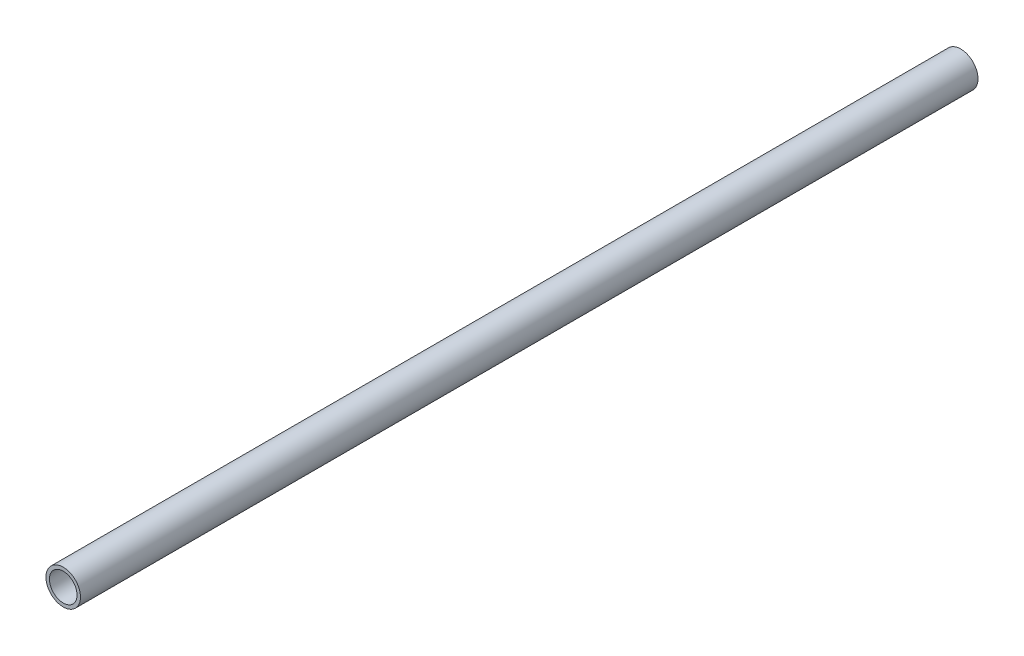
SolidWorks part; units mm, degrees
material "Alliage 1060"
ref_plane "Plan de face" through (0, 0, 0) normal (0, 0, 1) x (1, 0, 0)
ref_plane "Plan de dessus" through (0, 0, 0) normal (0, 1, 0) x (1, 0, 0)
ref_plane "Plan de droite" through (0, 0, 0) normal (1, 0, 0) x (0, 0, -1)
sketch "Esquisse1" plane through (0, 0, 0) normal (0, 0, 1) x (1, 0, 0)
  circle A0 centre (0, 0) radius 8
  circle A1 centre (0, 0) radius 10
  dimension "D1" = 20
  dimension "D2" = 2
extrude "Boss.-Extru.1" add sketch "Esquisse1" along normal blind 520
